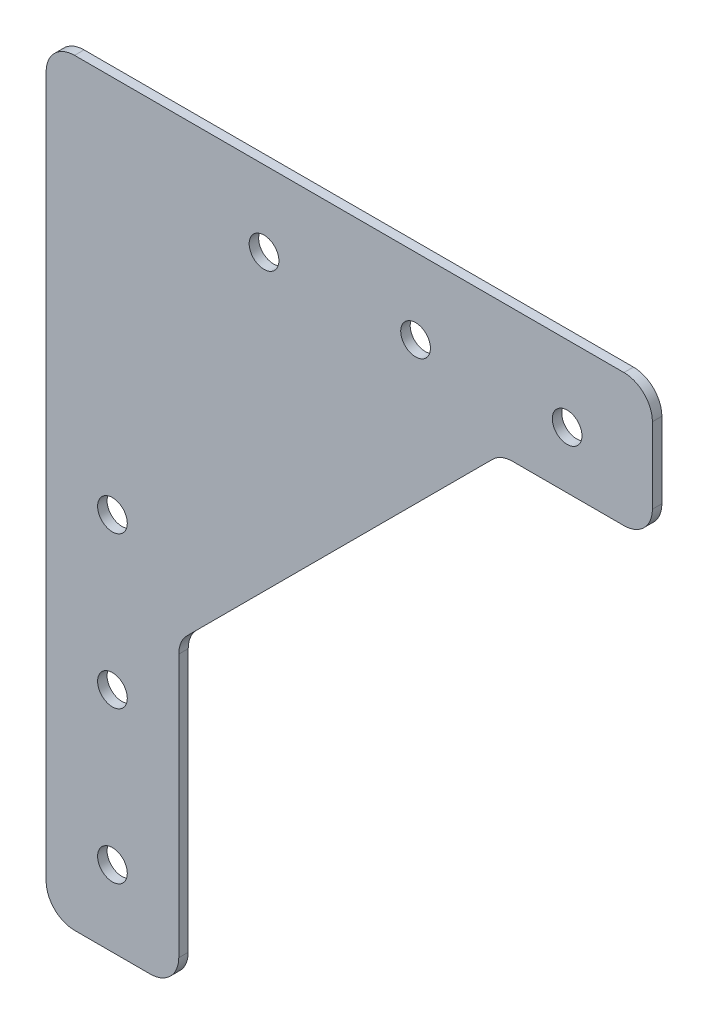
SolidWorks part; units mm, degrees
material "6061-T6 (SS)"
ref_plane "Front Plane" through (0, 0, 0) normal (0, 0, 1) x (1, 0, 0)
ref_plane "Top Plane" through (0, 0, 0) normal (0, 1, 0) x (1, 0, 0)
ref_plane "Right Plane" through (0, 0, 0) normal (1, 0, 0) x (0, 0, -1)
sketch "Sketch1" plane through (0, 0, 0) normal (0, 0, 1) x (1, 0, 0)
  line L8 (0, 0) -> (0, 127)
  line L14 (0, 127) -> (101.6, 127)
  line L15 (101.6, 127) -> (101.6, 104.775)
  line L17 (22.225, 0) -> (0, 0)
  line L18 (11.1125, 0) -> (11.1125, 127) construction
  line L19 (22.225, 0) -> (22.225, 50.8)
  line L20 (22.225, 50.8) -> (76.2, 104.775)
  line L21 (76.2, 104.775) -> (101.6, 104.775)
  circle A7 centre (11.1125, 63.5) radius 2.4892
  circle A8 centre (11.1125, 38.1) radius 2.4892
  circle A9 centre (11.1125, 12.7) radius 2.4892
  circle A11 centre (87.3125, 114.3) radius 2.4892
  circle A12 centre (61.9125, 114.3) radius 2.4892
  circle A13 centre (36.5125, 114.3) radius 2.4892
  dimension "D5" = 4.9784
  dimension "D7" = 12.7
  dimension "D1" = 22.225
  dimension "D2" = 127
  dimension "D3" = 101.6
  dimension "D4" = 3
  dimension "D6" = 25.4
  dimension "D8" = 3
  dimension "D9" = 12.7
  dimension "D10" = 25.4
  dimension "D11" = 25.4
  dimension "D12" = 45
  dimension "D13" = 25.4
extrude "Boss-Extrude1" add sketch "Sketch1" along normal mid plane 1.5875 contours L18 A7 | A7 L18 | L18 A9 | A9 L18 | A11
fillet "Fillet1" radius 4.7625 7 edges at (0, 127, 0) (0, 0, 0) (101.6, 104.775, 0) (76.2, 104.775, 0) (22.225, 50.8, 0) (22.225, 0, 0) (101.6, 127, 0)
